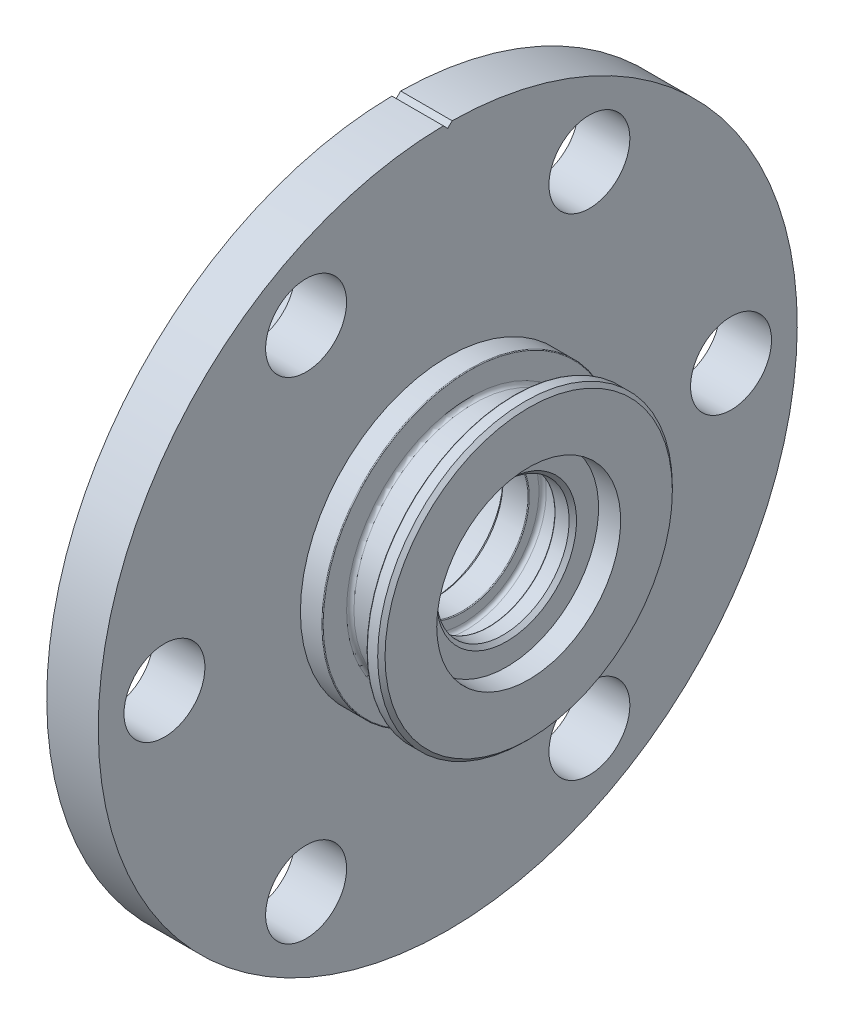
SolidWorks part; units mm, degrees
material "Алюминиевая бронза"
ref_plane "Спереди" through (0, 0, 0) normal (0, 0, 1) x (1, 0, 0)
ref_plane "Сверху" through (0, 0, 0) normal (0, 1, 0) x (1, 0, 0)
ref_plane "Справа" through (0, 0, 0) normal (1, 0, 0) x (0, 0, -1)
sketch "Эскиз1" plane through (0, 0, 0) normal (0, 0, 1) x (1, 0, 0)
  line L0 (0, 0) -> (68.8689, 0) construction
  line L1 (0, 15) -> (17, 15)
  line L2 (17, 15) -> (17, 9.5)
  line L3 (17.5, 9) -> (20.9, 9)
  line L4 (21, 9.1) -> (21, 10.4)
  line L5 (21.5, 10.9) -> (24, 10.9)
  line L6 (24.5, 10.4) -> (24.5, 9.1)
  line L7 (24.6, 9) -> (26.5, 9)
  line L8 (27, 9.5) -> (27, 12.5)
  line L9 (27, 12.5) -> (30, 12.5)
  line L10 (30, 12.5) -> (30, 19.525)
  line L11 (29.5, 20.025) -> (28.1, 20.025)
  line L12 (28, 19.925) -> (28, 16.75)
  line L13 (27.5, 16.25) -> (22.5, 16.25)
  line L14 (22, 16.75) -> (22, 19.925)
  line L15 (21.9, 20.025) -> (19, 20.025)
  line L16 (19, 20.025) -> (19, 47.5)
  line L17 (19, 47.5) -> (12, 47.5)
  line L18 (12, 47.5) -> (12, 25)
  line L19 (12, 25) -> (0, 25)
  line L20 (0, 25) -> (0, 15)
  line L21 (30, 19.525) -> (29.5, 20.025)
  line L22 (26.5, 9) -> (27, 9.5)
  line L23 (17, 9.5) -> (17.5, 9)
  arc A0 (28.1, 20.025) -> (28, 19.925) centre (28.1, 19.925) ccw
  arc A1 (22, 19.925) -> (21.9, 20.025) centre (21.9, 19.925) ccw
  arc A2 (28, 16.75) -> (27.5, 16.25) centre (27.5, 16.75) cw
  arc A3 (22.5, 16.25) -> (22, 16.75) centre (22.5, 16.75) cw
  arc A4 (24, 10.9) -> (24.5, 10.4) centre (24, 10.4) cw
  arc A5 (21, 10.4) -> (21.5, 10.9) centre (21.5, 10.4) cw
  arc A6 (24.5, 9.1) -> (24.6, 9) centre (24.6, 9.1) ccw
  arc A7 (20.9, 9) -> (21, 9.1) centre (20.9, 9.1) ccw
  point P6 (17, 9)
  point P11 (27, 9)
  point P14 (30, 20.025)
  point P29 (28, 16.25)
  point P32 (22, 16.25)
  point P41 (24.5, 10.9)
  point P44 (21, 10.9)
  dimension "D18" = 0.1
  dimension "D19" = 0.5
  dimension "D20" = 0.5
  dimension "D21" = 0.1
  dimension "D1" = 17
  dimension "D2" = 30
  dimension "D3" = 18
  dimension "D4" = 21.8
  dimension "D5" = 25
  dimension "D6" = 3
  dimension "D7" = 3.5
  dimension "D8" = 9
  dimension "D9" = 11
  dimension "D10" = 8
  dimension "D11" = 45
  dimension "D12" = 32.5
  dimension "D13" = 50
  dimension "D14" = 95
  dimension "D15" = 7
  dimension "D16" = 30
  dimension "D17" = 6
revolve "Повернуть1" add sketch "Эскиз1" angle 360 about L0
sketch "Эскиз2" plane through (19, 0, 0) normal (1, 0, 0) x (0, 0, -1)
  circle A0 centre (0, 0) radius 38.5 construction
  circle A1 centre (38.5, 0) radius 5.5
  dimension "D1" = 11
  dimension "D2" = 77
extrude "Вырез-Вытянуть1" cut sketch "Эскиз2" against normal through all
pattern_circular "Круговой массив1" count 6 over 360 about axis through (0, 0, 0) along (1, 0, 0) of "Вырез-Вытянуть1"
sketch "Эскиз3" plane through (19, 0, 0) normal (1, 0, 0) x (0, 0, -1)
  line L0 (-0.5963, 47.4963) -> (0, 46.9)
  line L1 (0, 46.9) -> (0.5963, 47.4963)
  circle A0 centre (0, 0) radius 47.5 construction
  arc A1 (0.5963, 47.4963) -> (-0.5963, 47.4963) centre (0, 0) ccw
  dimension "D1" = 90
  dimension "D2" = 0.6
extrude "Вырез-Вытянуть2" cut sketch "Эскиз3" against normal through all
sketch "Эскиз4" plane through (0, 0, 0) normal (-1, 0, 0) x (0, 0, 1)
  line L0 (0, 0) -> (-28.7491, 49.7949) construction
  line L1 (0, 0) -> (-56.5329, 0) construction
  line L2 (-22.4499, -11) -> (-10.198, -11)
  line L3 (-1.6987, 24.9422) -> (4.4273, 14.3318)
  circle A0 centre (0, 0) radius 15 construction
  circle A1 centre (0, 0) radius 25 construction
  arc A2 (4.4273, 14.3318) -> (-10.198, -11) centre (0, 0) ccw
  arc A3 (-1.6987, 24.9422) -> (-22.4499, -11) centre (0, 0) ccw
  dimension "D1" = 60
  dimension "D2" = 11
  dimension "D3" = 11
extrude "Вырез-Вытянуть3" cut sketch "Эскиз4" against normal blind 4
sketch "Эскиз5" plane through (4, 0, 0) normal (-1, 0, 0) x (0, 0, 1)
  line L0 (0, 0) -> (-29.8071, 0) construction
  line L1 (0, 0) -> (-16.4702, 28.5273) construction
  line L2 (-24.7878, -3.25) -> (-14.6437, -3.25)
  line L3 (-24.7878, 3.25) -> (-14.6437, 3.25)
  line L4 (-15.2085, 19.8419) -> (-10.1364, 11.0568)
  line L5 (-9.5793, 23.0919) -> (-4.5073, 14.3068)
  arc A0 (-1.6987, 24.9422) -> (-22.4499, -11) centre (0, 0) ccw construction
  arc A1 (4.4273, 14.3318) -> (-10.198, -11) centre (0, 0) ccw construction
  arc A2 (-9.5793, 23.0919) -> (-15.2085, 19.8419) centre (0, 0) ccw
  arc A3 (-4.5073, 14.3068) -> (-10.1364, 11.0568) centre (0, 0) ccw
  arc A4 (-24.7878, 3.25) -> (-24.7878, -3.25) centre (0, 0) ccw
  arc A5 (-14.6437, 3.25) -> (-14.6437, -3.25) centre (0, 0) ccw
  dimension "D1" = 60
  dimension "D2" = 6.5
extrude "Вырез-Вытянуть4" cut sketch "Эскиз5" against normal blind 3
sketch "Эскиз6" plane through (12, 0, 0) normal (-1, 0, 0) x (0, 0, 1)
  line L0 (0, 0) -> (0, 43) construction
  line L1 (0, 0) -> (37.2391, 21.5) construction
  line L2 (0, 0) -> (37.2391, -21.5) construction
  line L3 (0, 0) -> (-37.2391, -21.5) construction
  line L4 (25.2849, 30.3468) -> (38.9235, 6.7239) construction
  line L5 (-31.1506, -29.6418) -> (-41.2459, -12.1563) construction
  line L6 (29.8391, -30.9617) -> (41.7332, -10.3606) construction
  circle A0 centre (0, 0) radius 43 construction
  arc A1 (-11.1075, 37.9061) -> (11.1075, 37.9061) centre (0, 0) cw construction
  arc A2 (25.2849, 30.3468) -> (38.9235, 6.7239) centre (0, 0) cw construction
  arc A3 (29.8391, -30.9617) -> (41.7332, -10.3606) centre (0, 0) ccw construction
  arc A4 (-41.2459, -12.1563) -> (-31.1506, -29.6418) centre (0, 0) ccw construction
  text T0 "1"
  text T1 "2"
  text T2 "3"
  text T3 "4"
  dimension "D3" = 43
  dimension "D4" = 3.5
  dimension "D1" = 60
  dimension "D2" = 60
extrude "Вырез-Вытянуть5" cut sketch "Эскиз6" against normal blind 0.5
sketch "Эскиз7" plane through (0, 0, 0) normal (-1, 0, 0) x (0, 0, 1)
  line L0 (0, 0) -> (37.7462, -21.7928) construction
  line L1 (0, 0) -> (18.0213, -12.6187) construction
  line L2 (0, 0) -> (19.9388, -9.2976) construction
  line L3 (0, 0) -> (56.5586, 0) construction
  arc A0 (-11.3045, -18.8735) -> (18.0213, -12.6187) centre (0, 0) ccw construction
  arc A2 (-22.4499, -11) -> (-1.6987, 24.9422) centre (0, 0) ccw construction
  arc A3 (19.9388, -9.2976) -> (5.2468, 21.3652) centre (0, 0) ccw construction
  text T0 "ПЕРЕПУСК"
  text T1 "ГИДРАВЛИКА"
  dimension "D1" = 22
  dimension "D2" = 30
  dimension "D3" = 5
  dimension "D4" = 5
extrude "Вырез-Вытянуть6" cut sketch "Эскиз7" against normal blind 0.5
